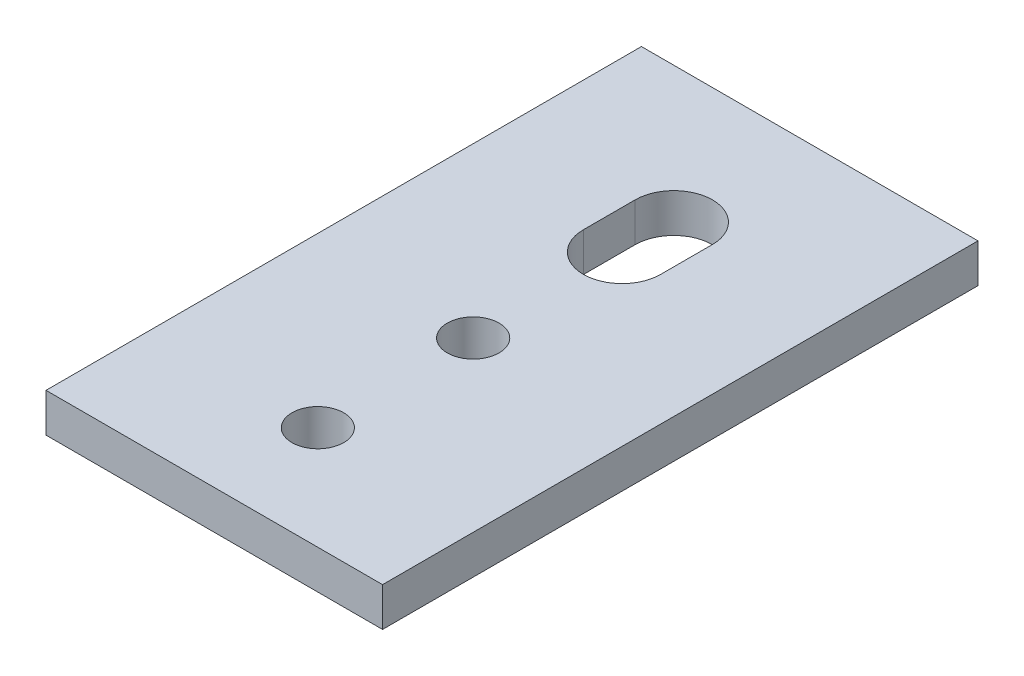
SolidWorks part; units mm, degrees
material "Brass"
ref_plane "Front Plane" through (0, 0, 0) normal (0, 0, 1) x (1, 0, 0)
ref_plane "Top Plane" through (0, 0, 0) normal (0, 1, 0) x (1, 0, 0)
ref_plane "Right Plane" through (0, 0, 0) normal (1, 0, 0) x (0, 0, -1)
sketch "Sketch1" plane through (0, 0, 0) normal (0, 1, 0) x (1, 0, 0)
  line L1 (-6.5, -11.5) -> (6.5, -11.5)
  line L2 (-6.5, -11.5) -> (-6.5, 11.5)
  line L3 (-6.5, 11.5) -> (6.5, 11.5)
  line L4 (6.5, -11.5) -> (6.5, 11.5)
  line L5 (-6.5, -11.5) -> (6.5, 11.5) construction
  line L6 (-6.5, 11.5) -> (6.5, -11.5) construction
  line L8 (-1.4932, 4.25) -> (-1.4932, 6.25)
  line L10 (1.4932, 4.25) -> (1.4932, 6.25)
  arc A0 (1.4932, 6.25) -> (-1.4932, 6.25) centre (0, 6.25) ccw
  arc A1 (-1.4932, 4.25) -> (1.4932, 4.25) centre (0, 4.25) ccw
  circle A2 centre (0, -1.5) radius 1
  circle A3 centre (0, -7.5) radius 1
  point P0 (0, 0)
  point P6 (0, 5.25)
  dimension "D5" = 13
  dimension "D6" = 2
  dimension "D7" = 19
  dimension "D8" = 2
  dimension "D1" = 13
  dimension "D2" = 23
  dimension "D3" = 6.25
  dimension "D4" = 2
extrude "Boss-Extrude1" add sketch "Sketch1" along normal blind 1.5
